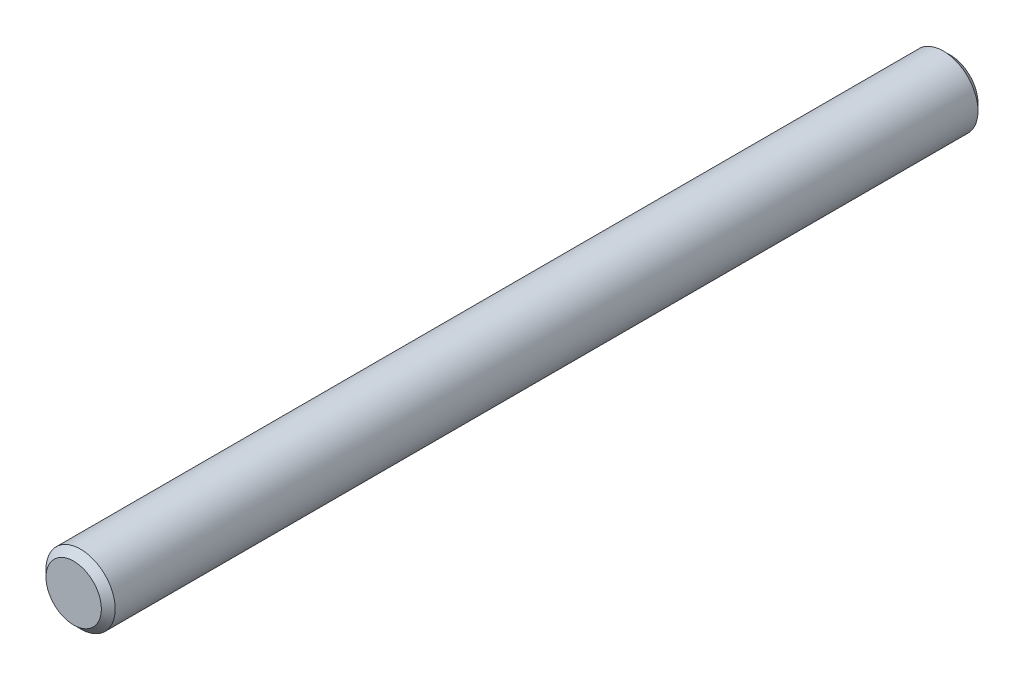
SolidWorks part; units mm, degrees
material "1023 Carbon Steel Sheet (SS)"
ref_plane "Front" through (0, 0, 0) normal (0, 0, 1) x (1, 0, 0)
ref_plane "Top" through (0, 0, 0) normal (0, 1, 0) x (1, 0, 0)
ref_plane "Right" through (0, 0, 0) normal (1, 0, 0) x (0, 0, -1)
sketch "Sketch1" plane through (0, 0, 0) normal (0, 0, 1) x (1, 0, 0)
  circle A0 centre (0, 0) radius 4.7625
  dimension "Diameter" = 9.525
sketch "Sketch2" plane through (0, 0, 0) normal (1, 0, 0) x (0, 0, -1)
  line L0 (-60.325, 0) -> (60.325, 0) construction
  line L1 (-9.525, 4.7625) -> (-9.525, -4.7625) construction
  line L2 (55, 0) -> (-55, 0) construction
  line L3 (9.525, 4.7625) -> (9.525, -4.7625) construction
  line L4 (-60.325, 4.7625) -> (-60.325, -4.7625) construction
  line L5 (60.325, 4.7625) -> (60.325, -4.7625) construction
  point P3 (-9.525, 0)
  point P8 (0, 0)
  point P9 (9.525, 0)
  point P15 (-60.325, 0)
  point P18 (60.325, 0)
  dimension "D1" = 9.525
  dimension "Length" = 120.65
  dimension "D2" = 50.8
  dimension "D3" = 50.8
sketch "Sketch3" plane through (0, 0, 0) normal (0, 0, 1) x (1, 0, 0)
  circle A0 centre (0, 0) radius 4.7625
  dimension "D1" = 9.525
extrude "Boss-Extrude1" add sketch "Sketch3" along normal mid plane 120.65
chamfer "Chamfer1" distance 0.9525 angle 45 2 edges at (4.7625, 0, -60.325) (4.7625, 0, 60.325)
equation "\"D1@Sketch3\" = \"Diameter@Sketch1\""
equation "\"D1@Boss-Extrude1\" = \"Length@Sketch2\""
equation "\"D1@Chamfer1\" = \"Diameter@Sketch1\" * .1"
equation "\"D1@Sketch2\" = \"Diameter@Sketch1\""
